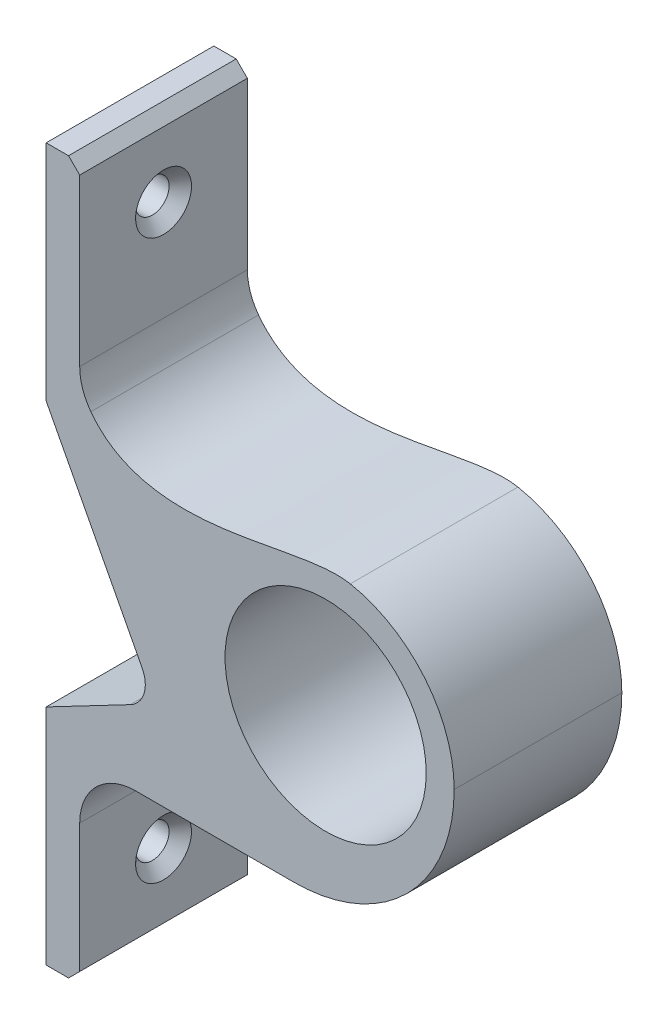
SolidWorks part; units mm, degrees
ref_plane "Front Plane" through (0, 0, 0) normal (0, 0, 1) x (1, 0, 0)
ref_plane "Top Plane" through (0, 0, 0) normal (0, 1, 0) x (1, 0, 0)
ref_plane "Right Plane" through (0, 0, 0) normal (1, 0, 0) x (0, 0, -1)
sketch "Sketch5" plane through (0, 0, 0) normal (0, 0, 1) x (1, 0, 0)
  line L0 (0, 87.2417) -> (0, -75.2249) construction
  line L1 (0, -23.7065) -> (0, -63.7065)
  line L2 (-19.4883, 13.4984) -> (0, 23.7065) construction
  line L3 (-19.4883, 13.4984) -> (0, -23.7065) construction
  line L4 (0, -23.7065) -> (15.0591, -15.8184)
  line L5 (0, 23.7065) -> (17.1683, -9.0692)
  line L6 (-19.4883, 13.4984) -> (19.4883, -13.4984) construction
  line L7 (0, -23.7065) -> (0, 23.7065) construction
  line L8 (0, -63.7065) -> (6, -63.7065)
  line L9 (6, -63.7065) -> (6, -38.7065)
  line L10 (0, 23.7065) -> (0, 63.7065)
  line L11 (0, 63.7065) -> (6, 63.7065)
  line L12 (6, 63.7065) -> (6, 32.0372)
  line L13 (16, -28.7065) -> (44.2935, -28.7065)
  line L14 (73, 0) -> (73, 15)
  line L15 (73, 15) -> (71, 15)
  line L16 (68, 12) -> (68, 0)
  line L17 (7.9971, 26.0411) -> (35.5948, -10.793)
  arc A0 (15.0591, -15.8184) -> (17.1683, -9.0692) centre (12.7391, -11.3893) ccw
  arc A1 (44.2935, -28.7065) -> (73, 0) centre (44.2935, 0) ccw
  arc A2 (68, 0) -> (35.5948, -10.793) centre (50, 0) cw
  arc A3 (6, -38.7065) -> (16, -28.7065) centre (16, -38.7065) cw
  arc A4 (6, 32.0372) -> (7.9971, 26.0411) centre (16, 32.0372) ccw
  arc A5 (71, 15) -> (68, 12) centre (71, 12) ccw
  circle A6 centre (50, 0) radius 18
  arc A7 (73, 0) -> (54.4129, 22.5727) centre (50, 0) ccw
  spline S0 degree 3 poles (54.4129, 22.5727) (48.6988, 23.6898) (29.1828, 17.0843) (12.2664, 20.3429) (7.9971, 26.0411) knots 0 0 0 0 0.577741 1 1 1 1
  point P3 (0, 0)
  point P32 (6, -28.7065)
  point P35 (6, 28.7065)
  point P38 (68, 15)
  dimension "D3" = 5
  dimension "D8" = 18
  dimension "D13" = 10
  dimension "D14" = 3
  dimension "D1" = 22
  dimension "D2" = 42
  dimension "D4" = 40
  dimension "D5" = 40
  dimension "D6" = 6
  dimension "D7" = 35
  dimension "D9" = 5
  dimension "D10" = 15
  dimension "D11" = 35
  dimension "D12" = 50
extrude "Boss-Extrude2" add sketch "Sketch5" along normal mid plane 30
sketch "Sketch1" plane through (0, 0, 0) normal (0, 0, 1) x (1, 0, 0)
  line L0 (0, 87.2417) -> (0, -75.2249) construction
  line L1 (0, -23.7065) -> (0, -63.7065)
  line L2 (-19.4883, 13.4984) -> (0, 23.7065) construction
  line L3 (-19.4883, 13.4984) -> (0, -23.7065) construction
  line L4 (0, -23.7065) -> (15.0591, -15.8184)
  line L5 (0, 23.7065) -> (17.1683, -9.0692)
  line L6 (-19.4883, 13.4984) -> (19.4883, -13.4984) construction
  line L7 (0, -23.7065) -> (0, 23.7065) construction
  line L8 (0, -63.7065) -> (6, -63.7065)
  line L9 (6, -63.7065) -> (6, -38.7065)
  line L10 (0, 23.7065) -> (0, 63.7065)
  line L11 (0, 63.7065) -> (6, 63.7065)
  line L12 (6, 63.7065) -> (6, 32.0372)
  line L13 (16, -28.7065) -> (44.2935, -28.7065)
  line L14 (73, 0) -> (73, 15)
  line L15 (73, 15) -> (71, 15)
  line L16 (68, 12) -> (68, 0)
  line L17 (7.9971, 26.0411) -> (35.5948, -10.793)
  arc A0 (15.0591, -15.8184) -> (17.1683, -9.0692) centre (12.7391, -11.3893) ccw
  arc A1 (44.2935, -28.7065) -> (73, 0) centre (44.2935, 0) ccw
  arc A2 (68, 0) -> (35.5948, -10.793) centre (50, 0) cw
  arc A3 (6, -38.7065) -> (16, -28.7065) centre (16, -38.7065) cw
  arc A4 (6, 32.0372) -> (7.9971, 26.0411) centre (16, 32.0372) ccw
  arc A5 (71, 15) -> (68, 12) centre (71, 12) ccw
  point P3 (0, 0)
  point P32 (6, -28.7065)
  point P35 (6, 28.7065)
  point P38 (68, 15)
  dimension "D3" = 5
  dimension "D8" = 18
  dimension "D13" = 10
  dimension "D14" = 3
  dimension "D1" = 22
  dimension "D2" = 42
  dimension "D4" = 40
  dimension "D5" = 40
  dimension "D6" = 6
  dimension "D7" = 35
  dimension "D9" = 5
  dimension "D10" = 15
  dimension "D11" = 35
  dimension "D12" = 50
extrude "Boss-Extrude1" [suppressed] add sketch "Sketch1" along normal mid plane 30
sketch "Sketch6" [suppressed] plane through (6, 0, 0) normal (1, 0, 0) x (0, 0, -1)
  circle A0 centre (0, -50) radius 3
  circle A1 centre (0, 50) radius 3
  dimension "D3" = 6
  dimension "D1" = 50
  dimension "D2" = 50
extrude "Cut-Extrude1" [suppressed] cut sketch "Sketch6" against normal through all
sketch "Sketch7" plane through (0, 0, 0) normal (1, 0, 0) x (0, 0, -1)
  circle A0 centre (0, -50) radius 3
  circle A1 centre (0, 50) radius 3
  dimension "D3" = 6
extrude "Cut-Extrude3" cut sketch "Sketch7" along normal through all
chamfer "Chamfer1" distance 2 angle 45 4 edges at (6, -53, 0) (6, 53, 0) (6, -63.7065, 0) (6, 63.7065, 0)
